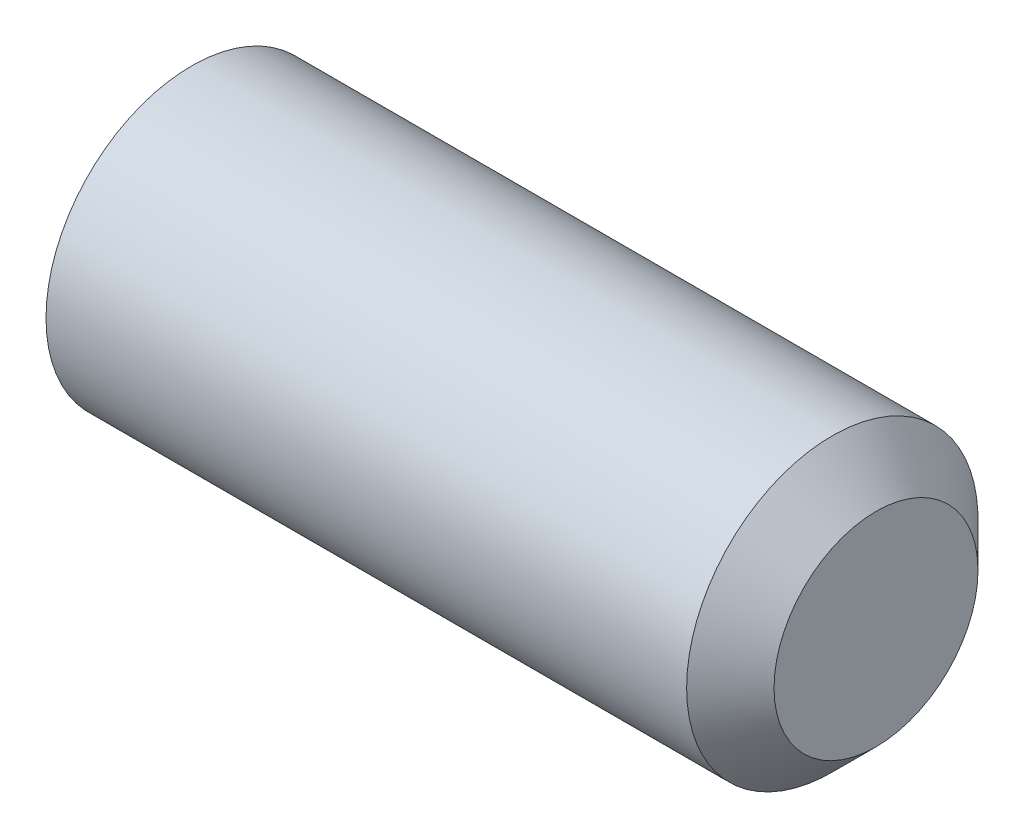
SolidWorks part; units mm, degrees
ref_plane "Plane1" through (0, 0, 0) normal (0, 0, 1) x (1, 0, 0)
ref_plane "Plane2" through (0, 0, 0) normal (0, 1, 0) x (1, 0, 0)
ref_plane "Plane3" through (0, 0, 0) normal (1, 0, 0) x (0, 0, -1)
sketch "BodySke" plane through (0, 0, 0) normal (0, 0, 1) x (1, 0, 0)
  line L0 (0, 0) -> (0, 2.055)
  line L1 (0, 2.055) -> (0.2569, 2.5)
  line L2 (0.2569, 2.5) -> (11.25, 2.5)
  line L3 (11.25, 2.5) -> (12, 1.75)
  line L4 (12, 0) -> (0, 0)
  line L5 (-12.7, 0) -> (88.9, 0) construction
  line L6 (12, 1.75) -> (12, 0)
  line L7 (12, 1.75) -> (12, 11.275) construction
  line L8 (0, -2.055) -> (0.2569, -2.5) construction
  line L9 (0.8, 15.875) -> (0.8, -3.175) construction
  line L10 (11.25, -2.5) -> (12, -1.75) construction
  dimension "Length" = 12
  dimension "Diameter" = 5
  dimension "Drive_ch_ang" = 60
  dimension "Minor_dia" = 4.11
  dimension "Cup_nose_ang" = 45
  dimension "Cup_dia" = 3.5
  dimension "Advance" = 0.8
revolve "BaseBody" add sketch "BodySke" angle 360 about L5
cosmetic thread "ThreadCosmetic" [suppressed] parameters "Thread_minor"=4.11
sketch "Sketch2" plane through (0, 0, 0) normal (-1, 0, 0) x (0, 0, 1)
  line L0 (0.7217, 1.25) -> (-0.7217, 1.25)
  line L1 (-0.7217, 1.25) -> (-1.4434, 0)
  line L2 (0.7217, 1.25) -> (1.4434, 0)
  line L3 (0.7217, -1.25) -> (1.4434, 0)
  line L4 (0.7217, -1.25) -> (-0.7217, -1.25)
  line L5 (-0.7217, -1.25) -> (-1.4434, 0)
  dimension "Hex_size" = 2.5
  dimension "D2" = 1.25
  dimension "D3" = 1.25
extrude "Hex" cut sketch "Sketch2" against normal blind 3
sketch "ThdSchSke" plane through (0, 0, 0) normal (0, 0, 1) x (1, 0, 0)
  line L0 (0.2569, -2.055) -> (-0.0547, -2.5)
  line L1 (0.2569, -2.055) -> (0.5685, -2.5)
  line L2 (0.5685, -2.5) -> (0.5685, -3.125)
  line L3 (-3.175, 0) -> (5.1513, 0) construction
  line L5 (0.5685, -3.125) -> (-0.0547, -3.125)
  line L6 (-0.0547, -3.125) -> (-0.0547, -2.5)
  line L8 (0.2569, 2.5) -> (0.2569, -2.5) construction
  dimension "Thread_minor" = 4.11
  dimension "Diameter" = 5
  dimension "SideAngle" = 55
  dimension "VeeAngle" = 70
  dimension "Overcut" = 6.25
revolve "ThreadSchematic" [suppressed] cut sketch "ThdSchSke" angle 360 about L3
pattern_linear "ThdSchPat" [suppressed]
equation "\"D2@Sketch2\" = \"Hex_size@Sketch2\" / 2"
equation "\"D3@Sketch2\" = \"Hex_size@Sketch2\" / 2"
equation "\"Thread_minor@ThreadCosmetic\" = \"Minor_dia@BodySke\""
equation "\"Thread_minor@ThdSchSke\" = \"Thread_minor@ThreadCosmetic\""
equation "\"Diameter@ThdSchSke\" = \"Diameter@BodySke\""
equation "\"Overcut@ThdSchSke\" = \"Diameter@BodySke\" * 1.25"
equation "\"Num_threads@ThdSchPat\" = int( (\"Length@BodySke\" - ( ( ( \"Diameter@BodySke\" - \"Minor_dia@BodySke\" ) * 0.5 ) / tan( \"Drive_ch_ang@BodySke\" * 0.017453292 ) ) - ( ( ( \"Diameter@BodySke\" - \"Cup_dia@BodySke\" ) * 0.5 ) * tan( \"Cup_nose_ang@BodySke\" * 0.017453292 ) ) ) / \"Advance@BodySke\" + 0.999 )  + 1"
equation "\"Advance@ThdSchPat\" = (\"Length@BodySke\" - ( ( ( \"Diameter@BodySke\" - \"Minor_dia@BodySke\" ) * 0.5 ) / tan( \"Drive_ch_ang@BodySke\" * 0.017453292 ) ) - ( ( ( \"Diameter@BodySke\" - \"Cup_dia@BodySke\" ) * 0.5 ) * tan( \"Cup_nose_ang@BodySke\" * 0.017453292 ) ) ) /  (\"Num_threads@ThdSchPat\" - 1) 'relax it"
equation "' \"Num_threads@ThdSchPat\" = \"Num_threads@ThdSchPat\" - sgn( \"Num_threads@ThdSchPat\" - 1) '---chamfered tips only---"
